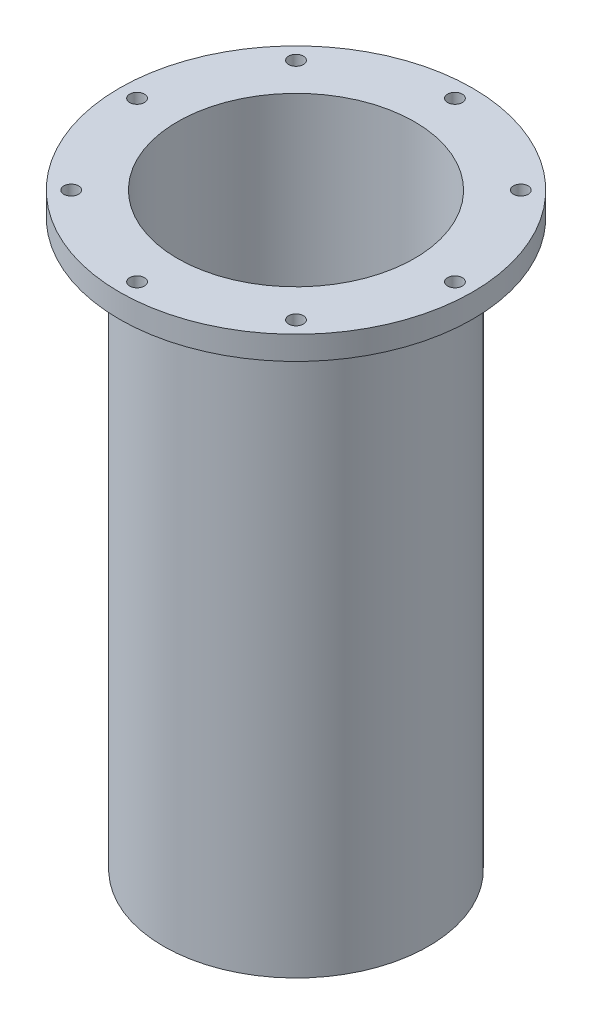
SolidWorks part; units mm, degrees
material "AISI 304"
ref_plane "Front Plane" through (0, 0, 0) normal (0, 0, 1) x (1, 0, 0)
ref_plane "Top Plane" through (0, 0, 0) normal (0, 1, 0) x (1, 0, 0)
ref_plane "Right Plane" through (0, 0, 0) normal (1, 0, 0) x (0, 0, -1)
sketch "Shell Profile" plane through (0, 0, 0) normal (0, 0, 1) x (1, 0, 0)
  line L0 (51.1302, 0) -> (51.1302, 254)
  line L1 (51.1302, 0) -> (57.15, 0)
  line L2 (57.15, 0) -> (57.15, 243.84)
  line L3 (57.15, 243.84) -> (76.2, 243.84)
  line L4 (76.2, 243.84) -> (76.2, 254)
  line L5 (76.2, 254) -> (51.1302, 254)
  line L6 (0, 0) -> (0, -75688.6337) construction
  dimension "Outer Flange Diameter" = 152.4
  dimension "Flange Thickness" = 10.16
  dimension "Pipe Outer Diameter" = 114.3
  dimension "Pipe Thickness" = 6.0198
  dimension "Pipe Length" = 254
revolve "Shell Revolve" add sketch "Shell Profile" angle 360 about L6
sketch "Bolt Holes Profile" plane through (0, 254, 0) normal (0, 1, 0) x (1, 0, 0)
  line L0 (0, -68.58) -> (0, 68.58) construction
  circle A0 centre (0, 68.58) radius 3.175
  circle A1 centre (48.4934, 48.4934) radius 3.175
  circle A2 centre (68.58, 0) radius 3.175
  circle A3 centre (48.4934, -48.4934) radius 3.175
  circle A4 centre (0, -68.58) radius 3.175
  circle A5 centre (-48.4934, -48.4934) radius 3.175
  circle A6 centre (-68.58, 0) radius 3.175
  circle A7 centre (-48.4934, 48.4934) radius 3.175
  point P4 (0, 0)
  point P23 (0, 0)
  dimension "Bolt Diameter" = 6.35
  dimension "Bolt Placement Diameter" = 137.16
  dimension "Number of Bolts" = 8
extrude "Bolt Holes" cut sketch "Bolt Holes Profile" against normal through all
